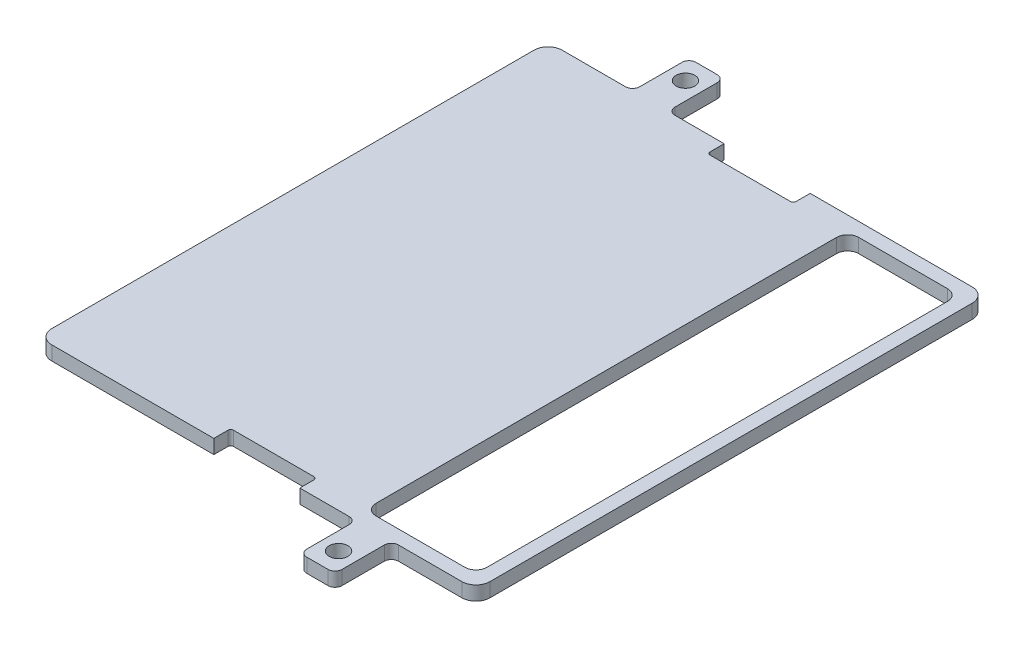
SolidWorks part; units mm, degrees
ref_plane "Front Plane" through (0, 0, 0) normal (0, 0, 1) x (1, 0, 0)
ref_plane "Top Plane" through (0, 0, 0) normal (0, 1, 0) x (1, 0, 0)
ref_plane "Right Plane" through (0, 0, 0) normal (1, 0, 0) x (0, 0, -1)
sketch "Sketch1" plane through (0, 0, 0) normal (0, 1, 0) x (1, 0, 0)
  line L0 (0, 64.0621) -> (0, -42.9514)
  line L1 (-36.957, -45.9994) -> (36.957, -45.9994)
  line L2 (-39.497, -43.4594) -> (-39.497, 43.4594)
  line L3 (-36.957, 45.9994) -> (36.957, 45.9994)
  line L4 (39.497, -43.4594) -> (39.497, 43.4594)
  line L5 (-39.497, -45.9994) -> (39.497, 45.9994) construction
  line L6 (-39.497, 45.9994) -> (39.497, -45.9994) construction
  line L11 (7.75, -45.9994) -> (7.75, -43.4514)
  line L12 (34.997, -43.4994) -> (18.997, -43.4994)
  line L13 (-61.2468, 0) -> (62.0626, 0)
  line L19 (41.5, 0) -> (51.66, 0)
  line L23 (36.997, -41.4994) -> (36.997, 41.4994)
  line L24 (34.997, 43.4994) -> (18.997, 43.4994)
  line L25 (16.997, -41.4994) -> (16.997, 41.4994)
  line L26 (36.997, -43.4994) -> (16.997, 43.4994) construction
  line L27 (36.997, 43.4994) -> (16.997, -43.4994) construction
  line L28 (7.75, -45.9994) -> (-7.75, -45.9994)
  line L30 (7.25, -42.9514) -> (-7.25, -42.9514)
  line L31 (-7.75, -45.9994) -> (-7.75, -43.4514)
  line L32 (0, -45.9994) -> (0, -62.7515)
  line L33 (7.75, 45.9994) -> (7.75, 43.4514)
  line L34 (7.75, 45.9994) -> (-7.75, 45.9994)
  line L35 (-7.75, 45.9994) -> (-7.75, 43.4514)
  line L36 (7.25, 42.9514) -> (-7.25, 42.9514)
  line L37 (17.907, 45.9994) -> (17.907, 54.8894)
  line L38 (17.907, -45.9994) -> (24.257, -45.9994)
  line L39 (17.907, -45.9994) -> (17.907, -54.8894)
  line L40 (19.177, -56.1594) -> (22.987, -56.1594)
  line L41 (24.257, -45.9994) -> (24.257, -54.8894)
  line L42 (19.177, 56.1594) -> (22.987, 56.1594)
  line L43 (24.257, 45.9994) -> (24.257, 54.8894)
  line L44 (17.907, 45.9994) -> (24.257, 45.9994)
  line L45 (-17.907, 45.9994) -> (-24.257, 45.9994)
  line L46 (-24.257, 45.9994) -> (-24.257, 54.8894)
  line L47 (-19.177, 56.1594) -> (-22.987, 56.1594)
  line L48 (-17.907, 45.9994) -> (-17.907, 54.8894)
  line L49 (-17.907, -45.9994) -> (-17.907, -54.8894)
  line L50 (-19.177, -56.1594) -> (-22.987, -56.1594)
  line L51 (-24.257, -45.9994) -> (-24.257, -54.8894)
  line L52 (-17.907, -45.9994) -> (-24.257, -45.9994)
  arc A0 (36.957, -45.9994) -> (39.497, -43.4594) centre (36.957, -43.4594) ccw
  arc A1 (-36.957, -45.9994) -> (-39.497, -43.4594) centre (-36.957, -43.4594) cw
  arc A2 (-39.497, 43.4594) -> (-36.957, 45.9994) centre (-36.957, 43.4594) cw
  arc A3 (36.957, 45.9994) -> (39.497, 43.4594) centre (36.957, 43.4594) cw
  arc A10 (16.997, -41.4994) -> (18.997, -43.4994) centre (18.997, -41.4994) ccw
  arc A11 (36.997, -41.4994) -> (34.997, -43.4994) centre (34.997, -41.4994) cw
  arc A12 (36.997, 41.4994) -> (34.997, 43.4994) centre (34.997, 41.4994) ccw
  arc A13 (18.997, 43.4994) -> (16.997, 41.4994) centre (18.997, 41.4994) ccw
  arc A14 (-7.25, -42.9514) -> (-7.75, -43.4514) centre (-7.25, -43.4514) ccw
  arc A15 (7.25, -42.9514) -> (7.75, -43.4514) centre (7.25, -43.4514) cw
  arc A16 (7.25, 42.9514) -> (7.75, 43.4514) centre (7.25, 43.4514) ccw
  arc A17 (-7.25, 42.9514) -> (-7.75, 43.4514) centre (-7.25, 43.4514) cw
  circle A18 centre (21.082, -52.3494) radius 1.6852
  arc A19 (22.987, -56.1594) -> (24.257, -54.8894) centre (22.987, -54.8894) ccw
  arc A20 (17.907, -54.8894) -> (19.177, -56.1594) centre (19.177, -54.8894) ccw
  circle A21 centre (21.082, 52.3494) radius 1.6852
  arc A22 (17.907, 54.8894) -> (19.177, 56.1594) centre (19.177, 54.8894) cw
  arc A23 (22.987, 56.1594) -> (24.257, 54.8894) centre (22.987, 54.8894) cw
  circle A24 centre (-21.082, 52.3494) radius 1.6852
  arc A25 (-22.987, 56.1594) -> (-24.257, 54.8894) centre (-22.987, 54.8894) ccw
  arc A26 (-17.907, 54.8894) -> (-19.177, 56.1594) centre (-19.177, 54.8894) ccw
  circle A27 centre (-21.082, -52.3494) radius 1.6852
  arc A28 (-17.907, -54.8894) -> (-19.177, -56.1594) centre (-19.177, -54.8894) cw
  arc A29 (-22.987, -56.1594) -> (-24.257, -54.8894) centre (-22.987, -54.8894) cw
  point P0 (0, 0)
  point P18 (0, 0)
  point P19 (26.997, 0)
  point P60 (-7.75, -42.9514)
  dimension "D3" = 2.54
  dimension "D6" = 20
  dimension "D8" = 6.35
  dimension "D11" = 2
  dimension "D13" = 0.5
  dimension "D16" = 1.27
  dimension "D1" = 78.994
  dimension "D2" = 91.9988
  dimension "D4" = 2.5
  dimension "D5" = 2.5
  dimension "D7" = 10.16
  dimension "D9" = 15.5
  dimension "D12" = 3.048
  dimension "D14" = 3.175
  dimension "D15" = 3.81
  dimension "D17" = 15.24
extrude "Boss-Extrude2" add sketch "Sketch1" along normal blind 2.54
fillet "Fillet1" radius 1.27 4 edges at (-17.907, 1.27, -45.9994) (-24.257, 1.27, -45.9994) (17.907, 1.27, 45.9994) (24.257, 1.27, 45.9994)
